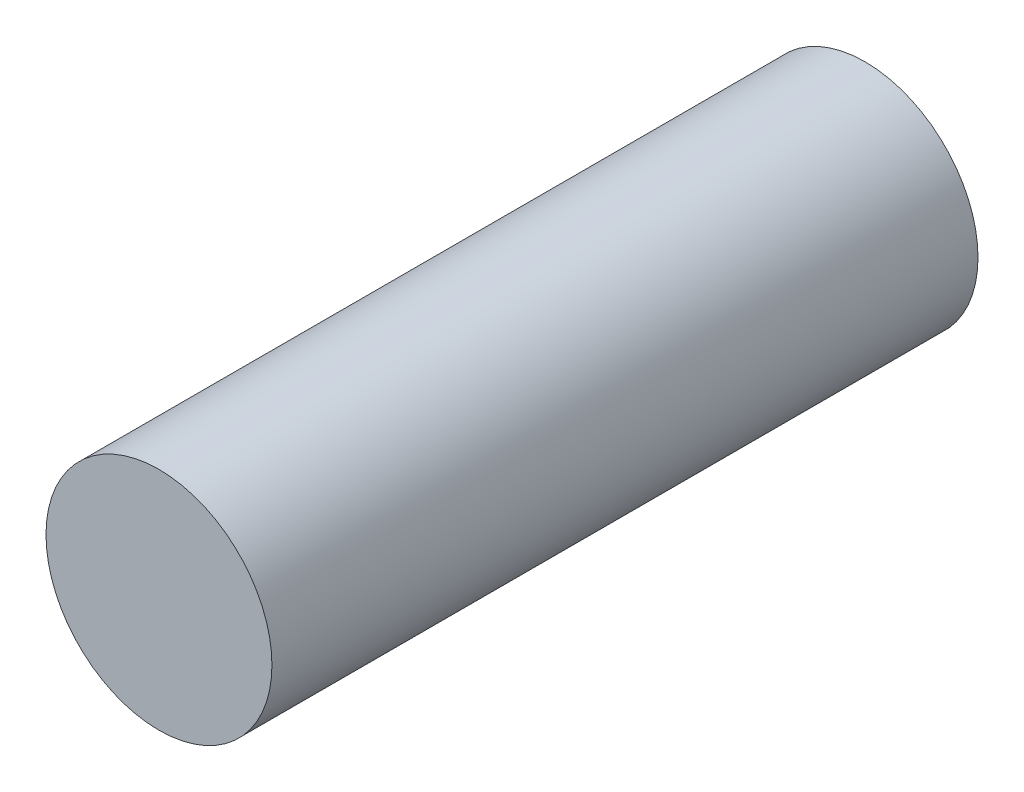
SolidWorks part; units mm, degrees
ref_plane "Front" through (0, 0, 0) normal (0, 0, 1) x (1, 0, 0)
ref_plane "Top" through (0, 0, 0) normal (0, 1, 0) x (1, 0, 0)
ref_plane "Right" through (0, 0, 0) normal (1, 0, 0) x (0, 0, -1)
sketch "Sketch1" plane through (0, 0, 0) normal (0, 0, 1) x (1, 0, 0)
  circle A0 centre (0, 0) radius 3.2
  dimension "D1" = 6.4
extrude "Boss-Extrude1" add sketch "Sketch1" along normal blind 20
